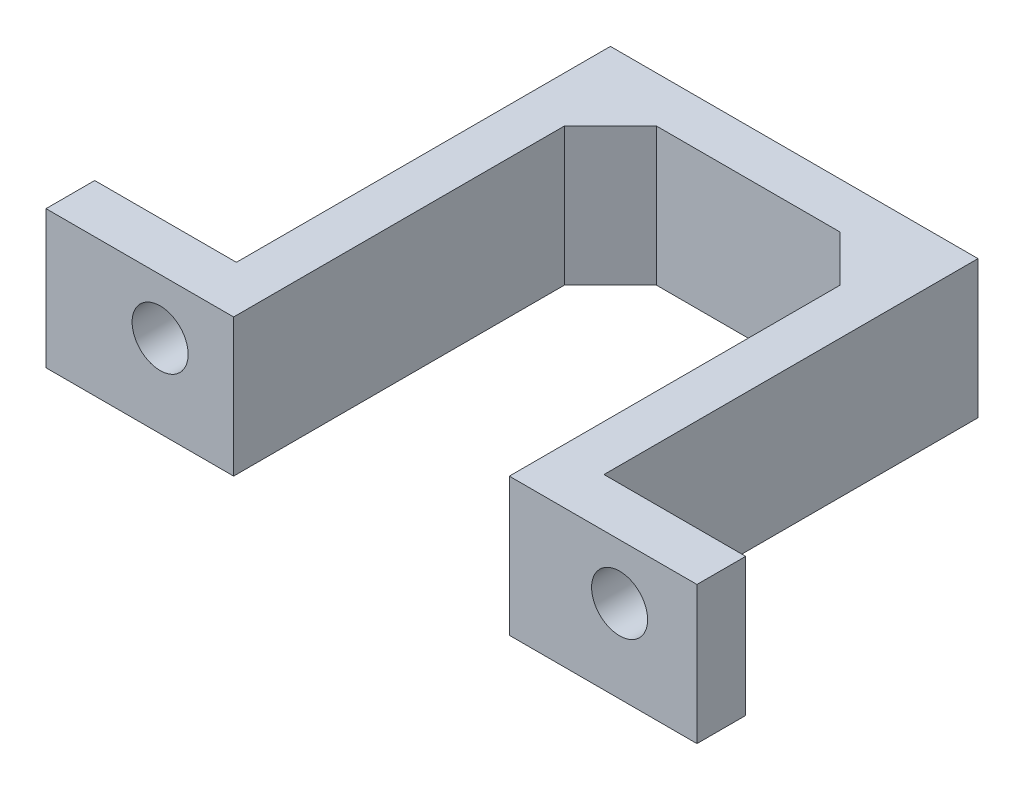
SolidWorks part; units mm, degrees
ref_plane "Front Plane" through (0, 0, 0) normal (0, 0, 1) x (1, 0, 0)
ref_plane "Top Plane" through (0, 0, 0) normal (0, 1, 0) x (1, 0, 0)
ref_plane "Right Plane" through (0, 0, 0) normal (1, 0, 0) x (0, 0, -1)
sketch "Sketch2" plane through (0, 0, 0) normal (0, 1, 0) x (1, 0, 0)
  line L0 (-13.5, 0) -> (6.5, 0)
  line L5 (11.5, -5) -> (11.5, -41)
  line L6 (11.5, -41) -> (31.9173, -41)
  line L7 (31.9173, -41) -> (31.9173, -35.699)
  line L8 (31.9173, -35.699) -> (16.5, -35.699)
  line L9 (16.5, -35.699) -> (16.5, 5)
  line L10 (16.5, 5) -> (-23.5, 5)
  line L11 (-23.5, 5) -> (-23.5, -35.699)
  line L12 (-23.5, -35.699) -> (-38.9173, -35.699)
  line L13 (-38.9173, -35.699) -> (-38.9173, -41)
  line L14 (-38.9173, -41) -> (-18.5, -41)
  line L15 (-18.5, -41) -> (-18.5, -5)
  line L16 (-23.5, -35.699) -> (-23.5, -53.6584) construction
  line L17 (-29.5, -29.038) -> (-29.5, -53.6584) construction
  line L18 (-29.5, -47.6505) -> (-23.5, -47.6505) construction
  line L19 (-3.5, 0) -> (-3.5, -26.0929) construction
  line L20 (-26.5, -47.6505) -> (-26.5, -68.2741) construction
  line L21 (23.5, -24.9282) -> (23.5, -62.6056) construction
  line L22 (20.5, -24.4655) -> (20.5, -49.1581) construction
  line L23 (26.5, -24.4655) -> (26.5, -49.1581) construction
  line L24 (20.5, -44.8687) -> (26.5, -44.8687) construction
  line L25 (23.5, -44.8687) -> (23.5, -42.6651) construction
  line L26 (-18.5, -5) -> (-13.5, 0)
  line L27 (6.5, 0) -> (11.5, -5)
  point P0 (-18.5, 0)
  point P1 (11.5, 0)
  point P23 (-3.5, -23.0301)
  point P34 (23.5, -43.7669)
  dimension "D1" = 30
  dimension "D2" = 5
  dimension "D3" = 5
  dimension "D4" = 46
  dimension "D5" = 6
  dimension "D6" = 50
  dimension "D7" = 6
extrude "Boss-Extrude1" add sketch "Sketch2" along normal blind 15
sketch "Sketch3" plane through (0, 0, 35.699) normal (0, 0, -1) x (-1, 0, 0)
  line L0 (-31.9173, 9) -> (43.2878, 9) construction
  line L1 (-31.9173, 15) -> (-31.9173, 0) construction
  line L2 (-16.5, 15) -> (23.5, 15) construction
  line L3 (-23.5, 15) -> (26.5, 15) construction
  line L4 (23.5, 15) -> (38.9173, 15) construction
  line L6 (-23.5, 15) -> (-23.5, -3.7562) construction
  line L7 (26.5, 15) -> (26.5, -7.565) construction
  line L8 (23.5, 15) -> (23.5, 0) construction
  circle A0 centre (26.5, 9) radius 3.05
  circle A1 centre (-23.5, 9) radius 3.05
  point P11 (1.5, 15)
  dimension "D4" = 6.1
  dimension "D1" = 6
  dimension "D2" = 50
  dimension "D3" = 3
extrude "Cut-Extrude1" cut sketch "Sketch3" against normal blind 15
